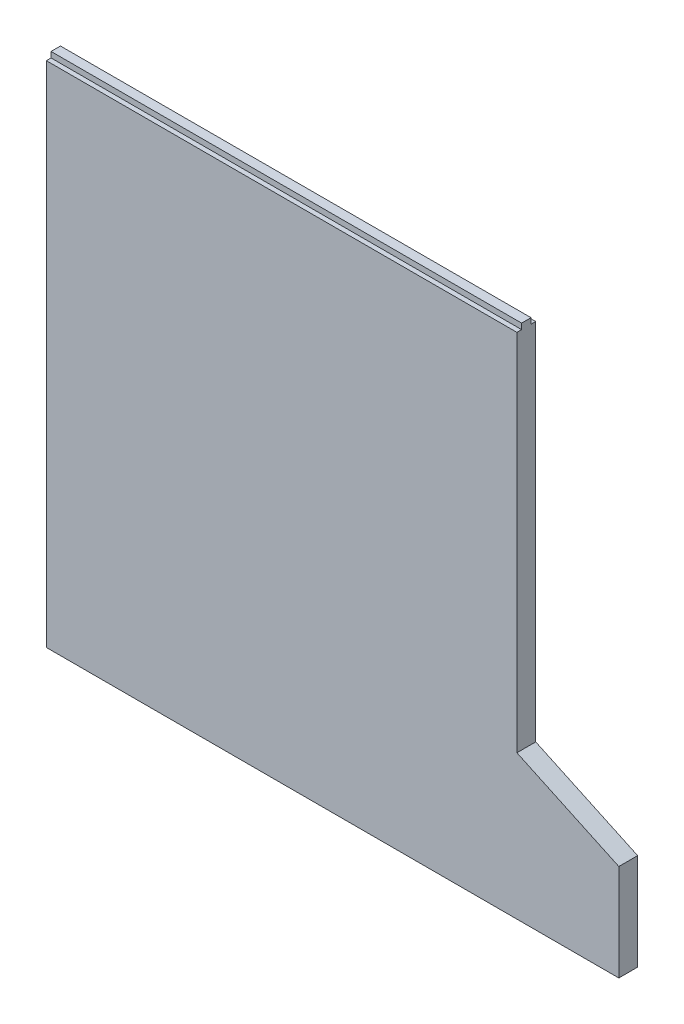
SolidWorks part; units mm, degrees
ref_plane "前基準面" through (0, 0, 0) normal (0, 0, 1) x (1, 0, 0)
ref_plane "上基準面" through (0, 0, 0) normal (0, 1, 0) x (1, 0, 0)
ref_plane "右基準面" through (0, 0, 0) normal (1, 0, 0) x (0, 0, -1)
sketch "草圖1" plane through (0, 0, 0) normal (0, 0, 1) x (1, 0, 0)
  line L0 (250, 76.5588) -> (304.1476, 51.3093)
  line L1 (0, 0) -> (154.1476, 0)
  line L2 (0, 0) -> (0, 350)
  line L3 (0, 350) -> (250, 350)
  line L4 (250, 76.5588) -> (250, 350)
  line L5 (304.1476, 51.3093) -> (304.1476, 0)
  line L6 (304.1476, 0) -> (154.1476, 0)
  dimension "D1" = 250
  dimension "D2" = 350
  dimension "D4" = 150
  dimension "D5" = 65
extrude "填料-伸長1" add sketch "草圖1" along normal blind 10
sketch "草圖3" plane through (250, 0, 0) normal (1, 0, 0) x (0, 0, -1)
  line L0 (-10, 76.5588) -> (-10, 350) construction
  line L1 (-10, 370) -> (-7.5, 370)
  line L2 (-10, 370) -> (-10, 270)
  line L3 (-10, 270) -> (-7.5, 270)
  line L4 (-7.5, 273) -> (-7.5, 270)
  line L5 (0, 76.5588) -> (0, 350) construction
  line L6 (0, 370) -> (-2.5, 370)
  line L7 (0, 370) -> (0, 270)
  line L8 (0, 270) -> (-2.5, 270)
  line L9 (-2.5, 273) -> (-2.5, 270)
  line L10 (-10, 270) -> (0, 270) construction
  line L11 (-10, 350) -> (0, 350) construction
  line L12 (-7.5, 273) -> (-2.5, 273)
  point P16 (-5, 273)
  dimension "D1" = 100
  dimension "D2" = 100
  dimension "D3" = 2.5
  dimension "D4" = 2.5
  dimension "D5" = 80
  dimension "D6" = 3
extrude "除料-伸長1" cut sketch "草圖3" against normal through all
